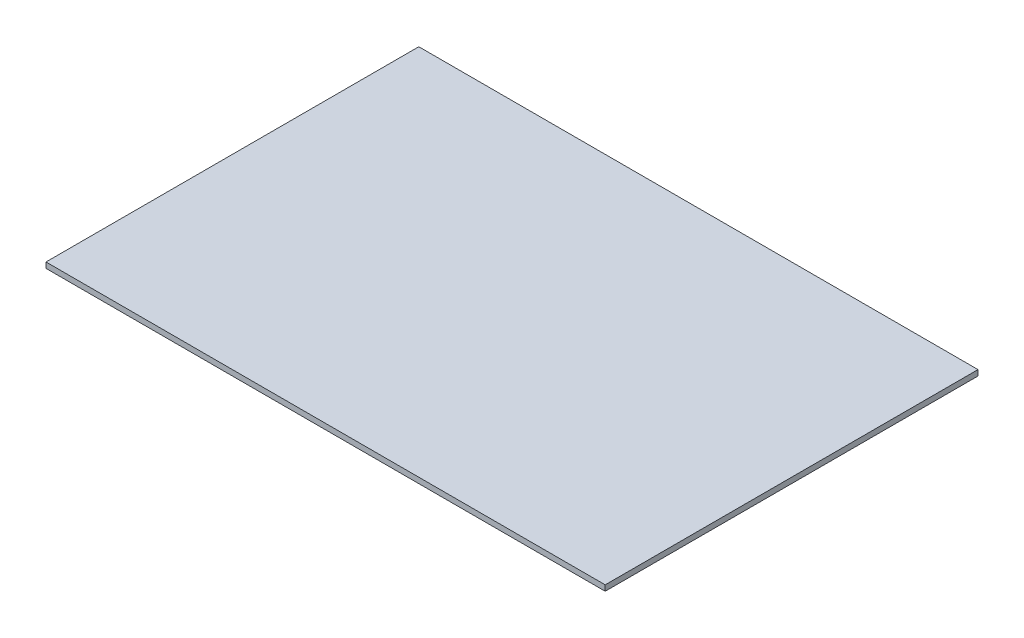
SolidWorks part; units mm, degrees
ref_plane "Front Plane" through (0, 0, 0) normal (0, 0, 1) x (1, 0, 0)
ref_plane "Top Plane" through (0, 0, 0) normal (0, 1, 0) x (1, 0, 0)
ref_plane "Right Plane" through (0, 0, 0) normal (1, 0, 0) x (0, 0, -1)
sketch "Sketch1" plane through (0, 0, 0) normal (0, 1, 0) x (1, 0, 0)
  line L1 (-150, 100) -> (150, 100)
  line L2 (-150, 100) -> (-150, -100)
  line L3 (-150, -100) -> (150, -100)
  line L4 (150, 100) -> (150, -100)
  line L5 (-150, 100) -> (150, -100) construction
  line L6 (-150, -100) -> (150, 100) construction
  point P0 (0, 0)
  dimension "D1" = 300
  dimension "D2" = 200
extrude "Boss-Extrude1" add sketch "Sketch1" along normal blind 3
